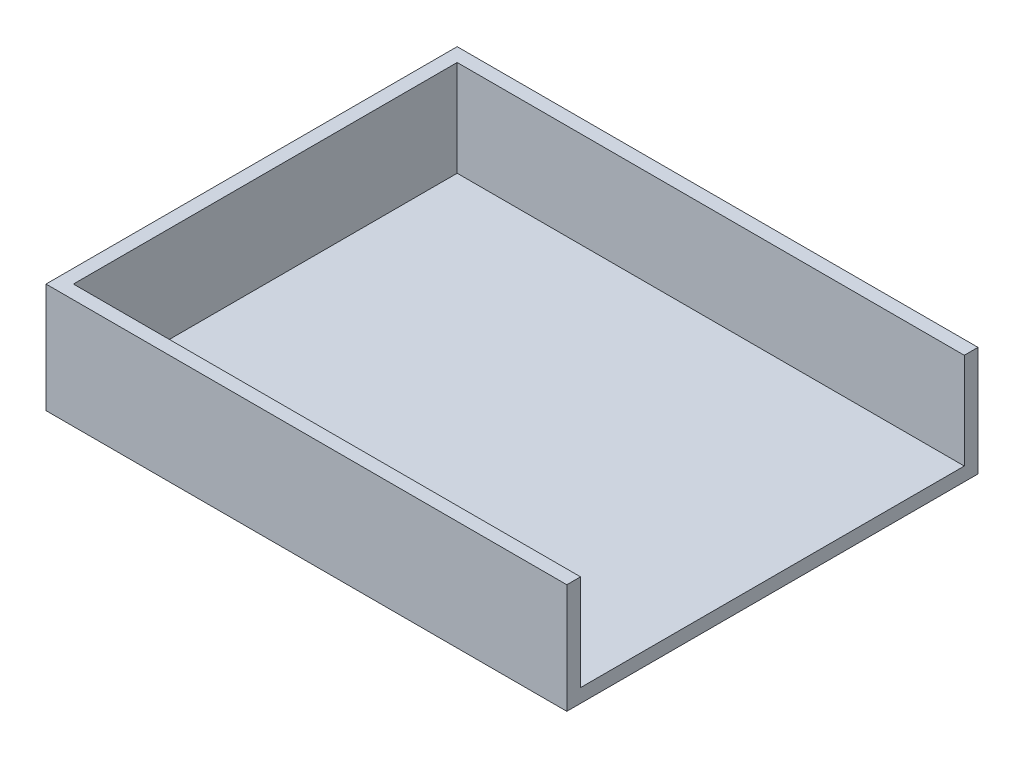
SolidWorks part; units mm, degrees
ref_plane "정면" through (0, 0, 0) normal (0, 0, 1) x (1, 0, 0)
ref_plane "윗면" through (0, 0, 0) normal (0, 1, 0) x (1, 0, 0)
ref_plane "우측면" through (0, 0, 0) normal (1, 0, 0) x (0, 0, -1)
sketch "스케치1" plane through (0, 0, 0) normal (0, 1, 0) x (1, 0, 0)
  line L1 (19, -15) -> (-19, -15)
  line L2 (19, -15) -> (19, 15)
  line L3 (19, 15) -> (-19, 15)
  line L4 (-19, -15) -> (-19, 15)
  line L5 (19, -15) -> (-19, 15) construction
  line L6 (19, 15) -> (-19, -15) construction
  point P0 (0, 0)
  dimension "D1" = 38
  dimension "D2" = 30
extrude "보스-돌출1" add sketch "스케치1" along normal blind 8
sketch "스케치2" plane through (0, 0, 0) normal (0, 1, 0) x (1, 0, 0)
  line L0 (19, 15) -> (-19, 15) construction
  line L1 (-18, 14) -> (19, 14)
  line L2 (-18, 14) -> (-18, -14)
  line L3 (-18, -14) -> (19, -14)
  line L4 (19, 14) -> (19, -14)
  line L5 (-19, 15) -> (-19, -15) construction
  dimension "D1" = 1
  dimension "D2" = 28
  dimension "D3" = 37
  dimension "D4" = 1
extrude "컷-돌출1" cut sketch "스케치2" along normal blind 7 from offset 1
sketch "스케치4" plane through (0, 0, 0) normal (0, 1, 0) x (1, 0, 0)
  line L1 (19, -15) -> (-19, -15)
  line L2 (19, -15) -> (19, 15)
  line L3 (19, 15) -> (-19, 15)
  line L4 (-19, -15) -> (-19, 15)
  line L5 (19, -15) -> (-19, 15) construction
  line L6 (19, 15) -> (-19, -15) construction
  point P0 (0, 0)
extrude "보스-돌출3" add sketch "스케치4" along normal blind 1 from offset 8 separate body
sketch "스케치5" plane through (0, 0, 0) normal (0, 1, 0) x (1, 0, 0)
  line L0 (-19, 15) -> (-19, -15) construction
  line L3 (19, 15) -> (-19, 15) construction
  circle A0 centre (-1, 0) radius 11
  dimension "D1" = 22
  dimension "D2" = 7
  dimension "D3" = 4
extrude "컷-돌출2" cut sketch "스케치5" against normal blind 1 from surface at 9 starting at face at (0, 9, 0)
sketch "스케치6" plane through (0, 9, 0) normal (0, 1, 0) x (1, 0, 0)
  line L4 (-19, 15) -> (-19, -15)
  line L5 (-19, -15) -> (19, -15)
  line L6 (19, -15) -> (19, 15)
  line L7 (19, 15) -> (-19, 15)
  line L8 (-19, 15) -> (-19, -15)
  line L9 (-19, -15) -> (19, -15)
  line L10 (19, -15) -> (19, 15)
  line L11 (19, 15) -> (-19, 15)
  dimension "D1" = 0
extrude "컷-돌출3" cut sketch "스케치6" against normal blind 1
